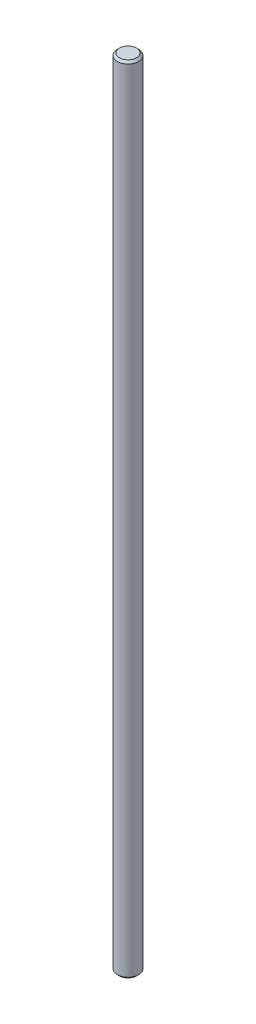
SolidWorks part; units mm, degrees
ref_plane "Front Plane" through (0, 0, 0) normal (0, 0, 1) x (1, 0, 0)
ref_plane "Top Plane" through (0, 0, 0) normal (0, 1, 0) x (1, 0, 0)
ref_plane "Right Plane" through (0, 0, 0) normal (1, 0, 0) x (0, 0, -1)
sketch "Sketch1" plane through (0, 0, 0) normal (0, 1, 0) x (1, 0, 0)
  circle A0 centre (0, 0) radius 5
  dimension "D1" = 10
extrude "Boss-Extrude1" add sketch "Sketch1" along normal blind 375
chamfer "Chamfer1" distance 1 angle 45 2 edges at (0, 375, 5) (0, 0, 5)
